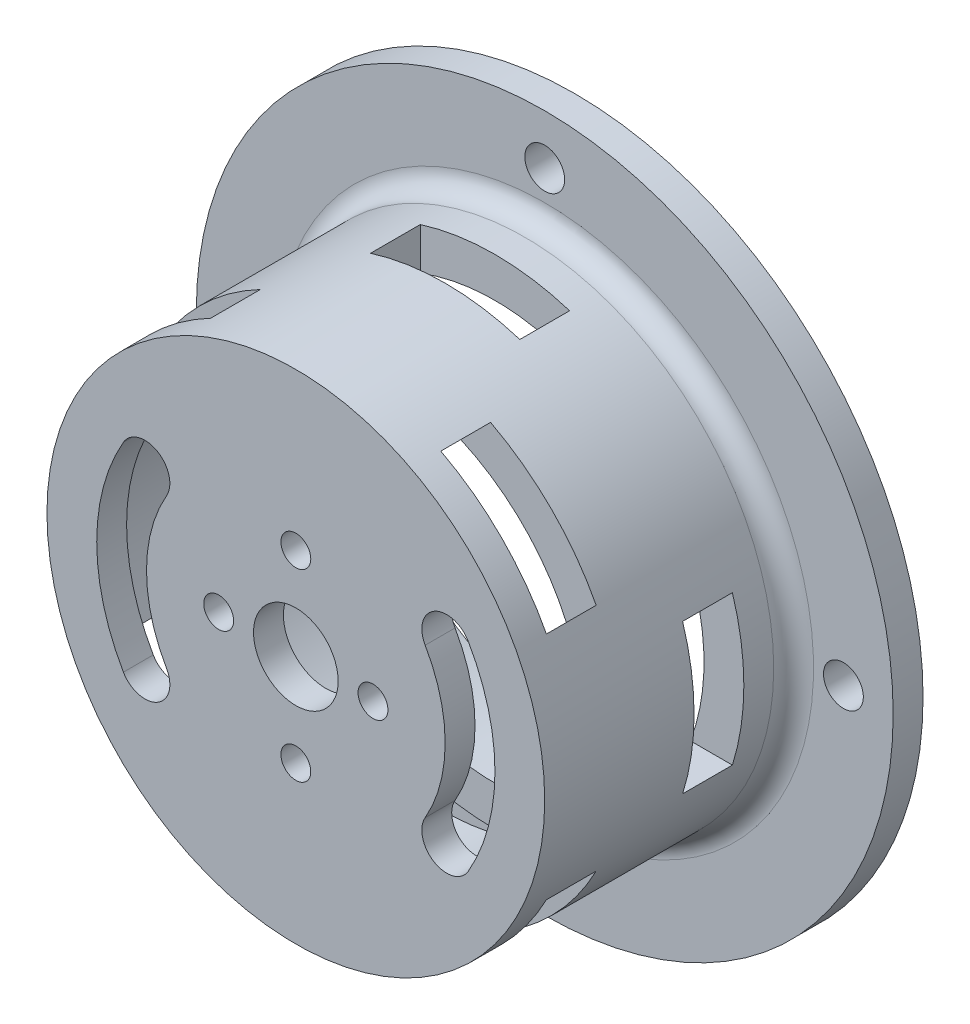
SolidWorks part; units mm, degrees
ref_plane "前视基准面" through (0, 0, 0) normal (0, 0, 1) x (1, 0, 0)
ref_plane "上视基准面" through (0, 0, 0) normal (0, 1, 0) x (1, 0, 0)
ref_plane "右视基准面" through (0, 0, 0) normal (1, 0, 0) x (0, 0, -1)
sketch "草图1" plane through (0, 0, 0) normal (0, 0, 1) x (1, 0, 0)
  circle A0 centre (0, 0) radius 21
  circle A1 centre (0, 0) radius 25
  dimension "D1" = 50
  dimension "D2" = 42
extrude "凸台-拉伸1" add sketch "草图1" along normal blind 25
sketch "草图2" plane through (0, 0, 25) normal (0, 0, 1) x (1, 0, 0)
  circle A1 centre (0, 0) radius 25
extrude "凸台-拉伸2" add sketch "草图2" along normal blind 3
sketch "草图3" plane through (0, 0, 28) normal (0, 0, 1) x (1, 0, 0)
  line L0 (0, 0) -> (0, -8.667) construction
  line L1 (0, 0) -> (-12.2601, 0) construction
  circle A0 centre (0, 0) radius 4.25
  circle A1 centre (0, 9.25) radius 1.5
  circle A2 centre (7.75, 0) radius 1.5
  circle A3 centre (0, -9.25) radius 1.5
  circle A4 centre (-7.75, 0) radius 1.5
  point P7 (0, 0)
  point P10 (0, 0)
  dimension "D3" = 3
  dimension "D4" = 3
  dimension "D5" = 8.5
  dimension "D1" = 9.25
  dimension "D2" = 7.75
extrude "切除-拉伸1" cut sketch "草图3" against normal blind 3
sketch "草图4" plane through (0, 0, 28) normal (0, 0, 1) x (1, 0, 0)
  line L0 (-15.1554, 8.75) -> (0, 0) construction
  line L1 (0, 0) -> (-15.1554, -8.75) construction
  line L2 (0, 0) -> (0, -18.3892) construction
  arc A0 (-15.1554, -8.75) -> (-15.1554, 8.75) centre (0, 0) cw construction
  arc A1 (-17.3205, 10) -> (-17.3205, -10) centre (0, 0) ccw
  arc A2 (-12.9904, 7.5) -> (-12.9904, -7.5) centre (0, 0) ccw
  arc A3 (-12.9904, 7.5) -> (-17.3205, 10) centre (-15.1554, 8.75) ccw
  arc A4 (-17.3205, -10) -> (-12.9904, -7.5) centre (-15.1554, -8.75) ccw
  arc A5 (15.1554, -8.75) -> (15.1554, 8.75) centre (0, 0) ccw construction
  arc A6 (17.3205, 10) -> (17.3205, -10) centre (0, 0) cw
  arc A7 (12.9904, 7.5) -> (12.9904, -7.5) centre (0, 0) cw
  arc A8 (12.9904, 7.5) -> (17.3205, 10) centre (15.1554, 8.75) cw
  arc A9 (17.3205, -10) -> (12.9904, -7.5) centre (15.1554, -8.75) cw
  point P3 (-17.5, 0)
  point P15 (17.5, 0)
  dimension "D1" = 15
  dimension "D2" = 20
  dimension "D3" = 60
extrude "切除-拉伸2" cut sketch "草图4" against normal blind 3
sketch "草图5" plane through (0, 0, 28) normal (0, 0, 1) x (1, 0, 0)
  line L0 (0, 0) -> (15.9988, 0)
  line L1 (0, 0) -> (17.6777, 17.6777)
  line L2 (0, 0) -> (-17.6777, 17.6777)
  circle A0 centre (0, 0) radius 25 construction
  dimension "D1" = 45
  dimension "D2" = 90
ref_plane "基准面1" through (17.6777, 17.6777, 28) normal (0.7071, 0.7071, 0) x (0.7071, -0.7071, 0)
sketch "草图6" plane through (17.6777, 17.6777, 28) normal (0.7071, 0.7071, 0) x (0.7071, -0.7071, 0)
  line L0 (0, 0) -> (11.3128, 0) construction
  line L1 (-7.5, 8) -> (7.5, 8)
  line L2 (-7.5, 8) -> (-7.5, 3)
  line L3 (-7.5, 3) -> (7.5, 3)
  line L4 (7.5, 8) -> (7.5, 3)
  line L5 (0, 3) -> (0, 8) construction
  line L6 (-7.5, 5.5) -> (7.5, 5.5) construction
  line L7 (-25, 0) -> (25, 0) construction
  point P0 (0, 5.5)
  point P6 (0, 0)
  point P7 (0, 0)
  dimension "D1" = 3
  dimension "D2" = 5
  dimension "D3" = 15
extrude "切除-拉伸3" cut sketch "草图6" against normal blind 63
ref_plane "基准面2" through (-17.6777, 17.6777, 28) normal (-0.7071, 0.7071, 0) x (0, 0, 1)
sketch "草图8" plane through (-17.6777, 17.6777, 28) normal (-0.7071, 0.7071, 0) x (0, 0, 1)
  line L1 (-8, 7.5) -> (-3, 7.5)
  line L2 (-8, 7.5) -> (-8, -7.5)
  line L3 (-8, -7.5) -> (-3, -7.5)
  line L4 (-3, 7.5) -> (-3, -7.5)
  line L5 (-5.5, -7.5) -> (-5.5, 7.5) construction
  line L6 (-8, 0) -> (-3, 0) construction
  line L7 (0, -25) -> (0, 25) construction
  point P0 (-5.5, 0)
  point P4 (0, 0)
  point P5 (0, 0)
  dimension "D1" = 5
  dimension "D2" = 15
  dimension "D3" = 3
extrude "切除-拉伸4" cut sketch "草图8" against normal blind 63
sketch "草图9" plane through (0, 0, 0) normal (1, 0, 0) x (0, 0, -1)
  line L0 (0, -25) -> (0, 25) construction
  line L1 (-13, 7.5) -> (-8, 7.5)
  line L2 (-13, 7.5) -> (-13, -7.5)
  line L3 (-13, -7.5) -> (-8, -7.5)
  line L4 (-8, 7.5) -> (-8, -7.5)
  line L5 (-10.5, -7.5) -> (-10.5, 7.5) construction
  line L6 (-13, 0) -> (-8, 0) construction
  point P0 (-10.5, 0)
  point P4 (0, 0)
  dimension "D1" = 5
  dimension "D2" = 15
  dimension "D3" = 8
extrude "切除-拉伸5" cut sketch "草图9" against normal blind 63
pattern_circular "阵列(圆周)2" count 4 over 360 about axis through (0, 0, 0) along (0, 0, 1) of "切除-拉伸5"
sketch "草图10" plane through (0, 0, 0) normal (0, 0, -1) x (-1, 0, 0)
  circle A0 centre (0, 0) radius 35
  circle A2 centre (0, 0) radius 21
  dimension "D1" = 70
extrude "凸台-拉伸3" add sketch "草图10" against normal blind 3
sketch "草图11" plane through (0, 0, 0) normal (0, 0, -1) x (-1, 0, 0)
  circle A0 centre (0, 0) radius 30 construction
  circle A1 centre (0, 30) radius 2
  circle A2 centre (30, 0) radius 2
  circle A3 centre (0, -30) radius 2
  circle A4 centre (-30, 0) radius 2
  dimension "D1" = 4
  dimension "D2" = 60
  dimension "D3" = 4
extrude "切除-拉伸6" cut sketch "草图11" against normal blind 3
fillet "圆角1" radius 2 1 edges at (-25, 0, 3)
